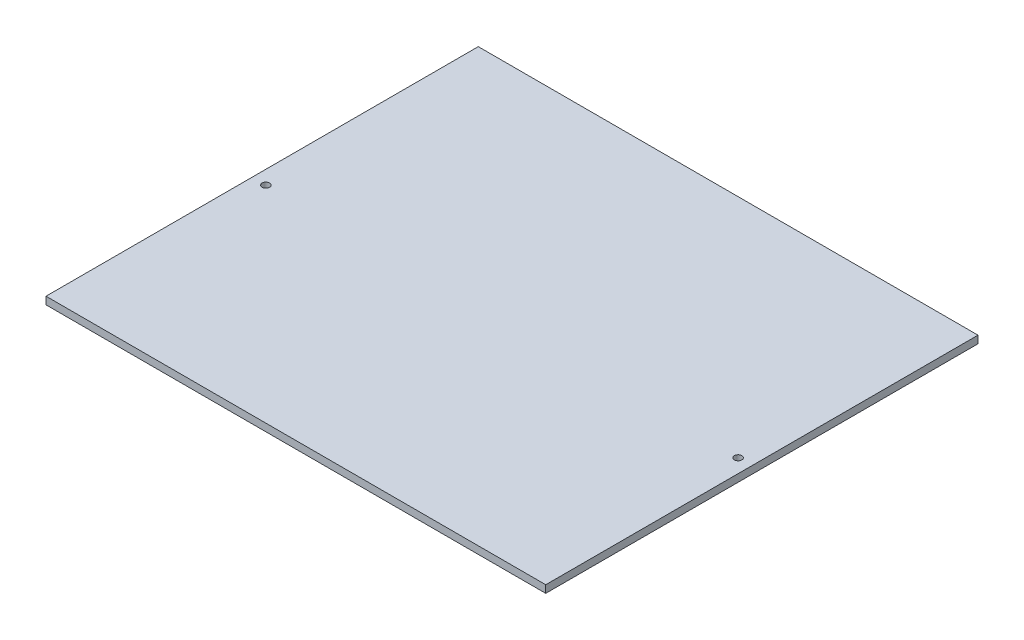
SolidWorks part; units mm, degrees
ref_plane "Front Plane" through (0, 0, 0) normal (0, 0, 1) x (1, 0, 0)
ref_plane "Top Plane" through (0, 0, 0) normal (0, 1, 0) x (1, 0, 0)
ref_plane "Right Plane" through (0, 0, 0) normal (1, 0, 0) x (0, 0, -1)
sketch "Sketch1" plane through (0, 0, 0) normal (0, 1, 0) x (1, 0, 0)
  line L1 (-100, 86.5) -> (100, 86.5)
  line L2 (-100, 86.5) -> (-100, -86.5)
  line L3 (-100, -86.5) -> (100, -86.5)
  line L4 (100, 86.5) -> (100, -86.5)
  line L5 (-100, 86.5) -> (100, -86.5) construction
  line L6 (-100, -86.5) -> (100, 86.5) construction
  point P0 (0, 0)
  dimension "D1" = 200
  dimension "D2" = 173
extrude "Boss-Extrude1" add sketch "Sketch1" along normal blind 3
sketch "Sketch3" plane through (0, 3, 0) normal (0, 1, 0) x (1, 0, 0)
  line L0 (-100, -86.5) -> (100, -86.5) construction
  line L1 (100, -86.5) -> (100, 86.5) construction
  line L2 (0, -1.65) -> (0, 1.65) construction
  circle A0 centre (94.5, -4) radius 1.5
  circle A1 centre (-94.5, -4) radius 1.5
  dimension "D3" = 3
  dimension "D1" = 82.5
  dimension "D2" = 5.5
extrude "Cut-Extrude2" cut sketch "Sketch3" against normal through all
sketch "Sketch5" plane through (0, 3, 0) normal (0, 1, 0) x (1, 0, 0)
